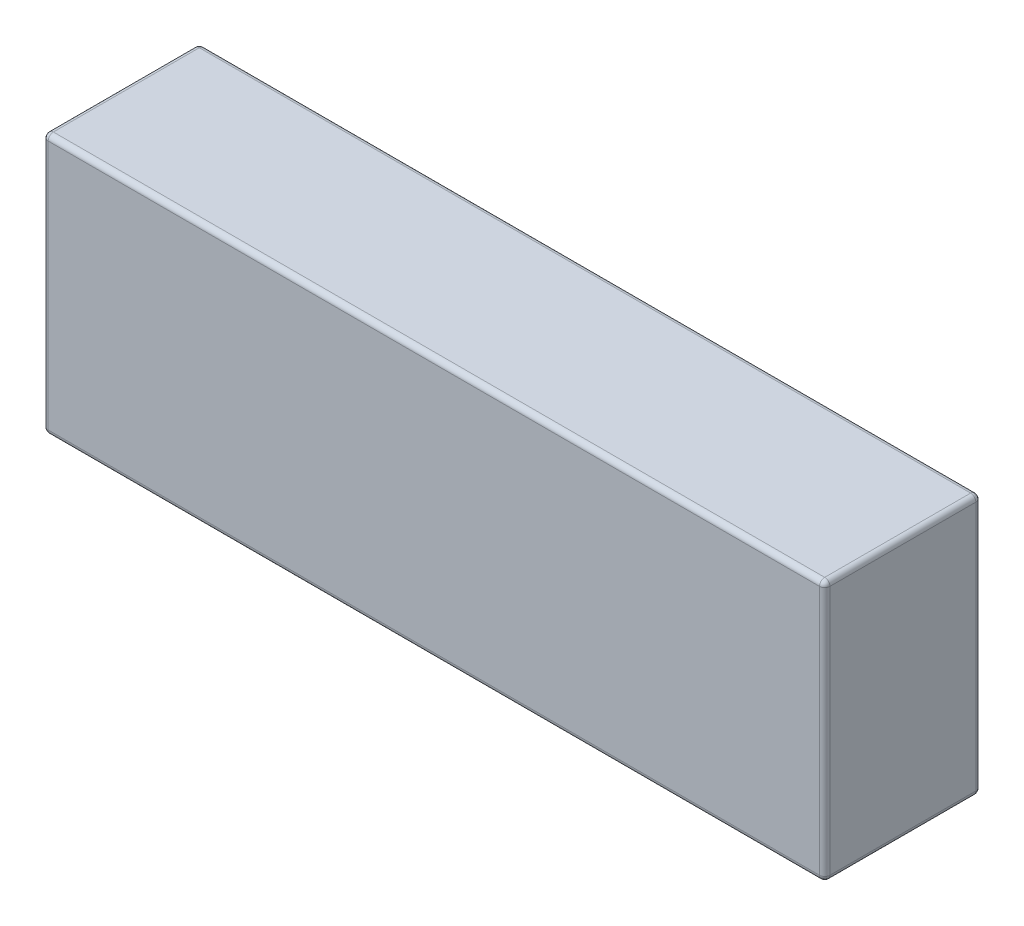
SolidWorks part; units mm, degrees
material "Maple"
ref_plane "Front Plane" through (0, 0, 0) normal (0, 0, 1) x (1, 0, 0)
ref_plane "Top Plane" through (0, 0, 0) normal (0, 1, 0) x (1, 0, 0)
ref_plane "Right Plane" through (0, 0, 0) normal (1, 0, 0) x (0, 0, -1)
sketch "Sketch1" plane through (0, 0, 0) normal (0, 0, 1) x (1, 0, 0)
  line L1 (-75, 25) -> (75, 25)
  line L2 (-75, 25) -> (-75, -25)
  line L3 (-75, -25) -> (75, -25)
  line L4 (75, 25) -> (75, -25)
  line L5 (-75, 25) -> (75, -25) construction
  line L6 (-75, -25) -> (75, 25) construction
  point P0 (0, 0)
  dimension "D1" = 50
  dimension "D2" = 150
extrude "Boss-Extrude1" add sketch "Sketch1" along normal blind 28
sketch "Sketch3" plane through (0, 0, 28) normal (0, 0, 1) x (1, 0, 0)
  line L1 (-75, 25) -> (75, 25)
  line L2 (-75, 25) -> (-75, -25)
  line L3 (-75, -25) -> (75, -25)
  line L4 (75, 25) -> (75, -25)
  line L5 (-75, 25) -> (75, -25) construction
  line L6 (-75, -25) -> (75, 25) construction
  point P0 (0, 0)
extrude "Boss-Extrude2" add sketch "Sketch3" along normal blind 1
sketch "Sketch4" plane through (0, 0, 0) normal (0, 0, -1) x (-1, 0, 0)
  line L1 (-75, 25) -> (75, 25)
  line L2 (-75, 25) -> (-75, -25)
  line L3 (-75, -25) -> (75, -25)
  line L4 (75, 25) -> (75, -25)
  line L5 (-75, 25) -> (75, -25) construction
  line L6 (-75, -25) -> (75, 25) construction
  point P0 (0, 0)
extrude "Boss-Extrude3" add sketch "Sketch4" along normal blind 1
fillet "Fillet1" radius 1 12 edges at (-75, 25, 14) (-75, -25, 14) (75, -25, 14) (0, -25, 29) (-75, 0, 29) (0, -25, -1) (75, 0, -1) (0, 25, -1) (-75, 0, -1) (0, 25, 29) (75, 25, 14) (75, 0, 29)
sketch "Sketch5" plane through (0, 0, -1) normal (0, 0, -1) x (-1, 0, 0)
  line L0 (-92.6765, 14.1347) -> (-92.6765, 169.4681) construction
sketch "Sketch6" plane through (0, 0, 29) normal (0, 0, 1) x (1, 0, 0)
  line L0 (13.3076, 93.2758) -> (166.641, 93.2758) construction
sketch "Sketch7" plane through (0, 0, -1) normal (0, 0, -1) x (-1, 0, 0)
  line L0 (0, 25) -> (0, -25)
  line L1 (-74, 25) -> (74, 25) construction
  line L2 (74, -25) -> (-74, -25) construction
  line L4 (-25, 25) -> (25, 25)
  line L5 (-25, 25) -> (-25, -25)
  line L6 (-25, -25) -> (25, -25)
  line L7 (25, 25) -> (25, -25)
  line L8 (-25, 25) -> (25, -25) construction
  line L9 (-25, -25) -> (25, 25) construction
  point P6 (0, 0)
  dimension "D1" = 50
